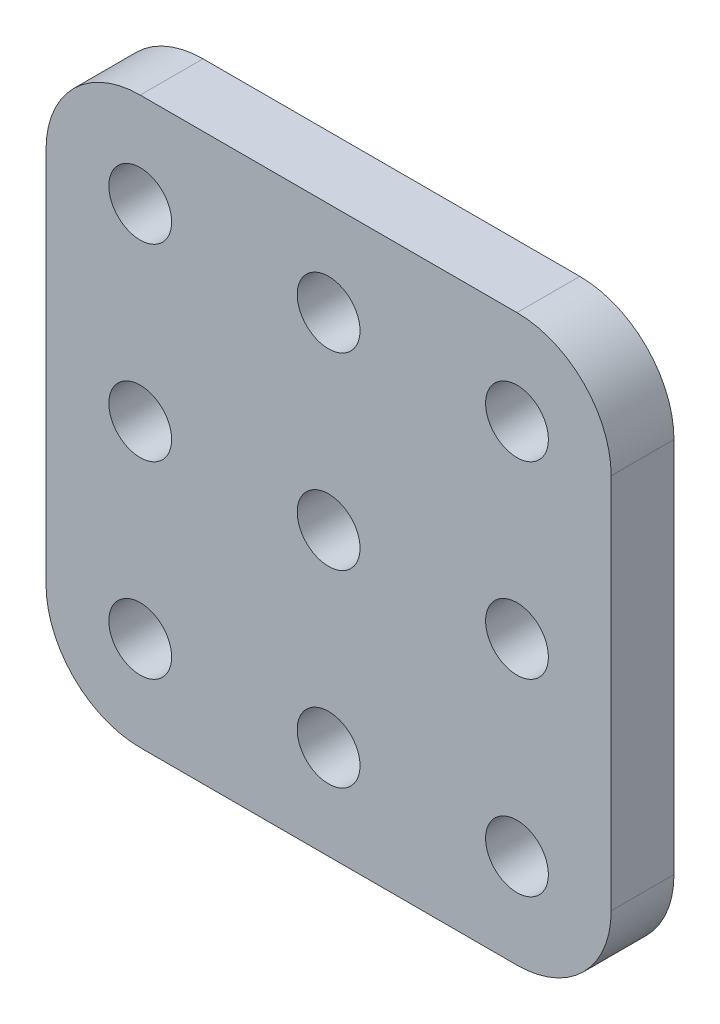
SolidWorks part; units mm, degrees
ref_plane "Alzado" through (0, 0, 0) normal (0, 0, 1) x (1, 0, 0)
ref_plane "Planta" through (0, 0, 0) normal (0, 1, 0) x (1, 0, 0)
ref_plane "Vista lateral" through (0, 0, 0) normal (1, 0, 0) x (0, 0, -1)
sketch "Model" plane through (0, 0, 0) normal (0, 0, 1) x (1, 0, 0)
  line L0 (-105.9434, 101.0565) -> (-105.9434, 83.0565)
  line L1 (-101.4434, 78.5565) -> (-83.4434, 78.5565)
  line L2 (-78.9434, 83.0565) -> (-78.9434, 101.0565)
  line L3 (-83.4434, 105.5565) -> (-101.4434, 105.5565)
  circle A0 centre (-101.4434, 101.0565) radius 1.5
  circle A1 centre (-92.4434, 101.0565) radius 1.5
  circle A2 centre (-83.4434, 101.0565) radius 1.5
  circle A3 centre (-101.4434, 92.0565) radius 1.5
  circle A4 centre (-92.4434, 92.0565) radius 1.5
  circle A5 centre (-83.4434, 92.0565) radius 1.5
  circle A6 centre (-101.4434, 83.0565) radius 1.5
  circle A7 centre (-92.4434, 83.0565) radius 1.5
  circle A8 centre (-83.4434, 83.0565) radius 1.5
  arc A9 (-101.4434, 105.5565) -> (-105.9434, 101.0565) centre (-101.4434, 101.0565) ccw
  arc A10 (-78.9434, 101.0565) -> (-83.4434, 105.5565) centre (-83.4434, 101.0565) ccw
  arc A11 (-105.9434, 83.0565) -> (-101.4434, 78.5565) centre (-101.4434, 83.0565) ccw
  arc A12 (-83.4434, 78.5565) -> (-78.9434, 83.0565) centre (-83.4434, 83.0565) ccw
extrude "Saliente-Extruir1" add sketch "Model" along normal blind 3
